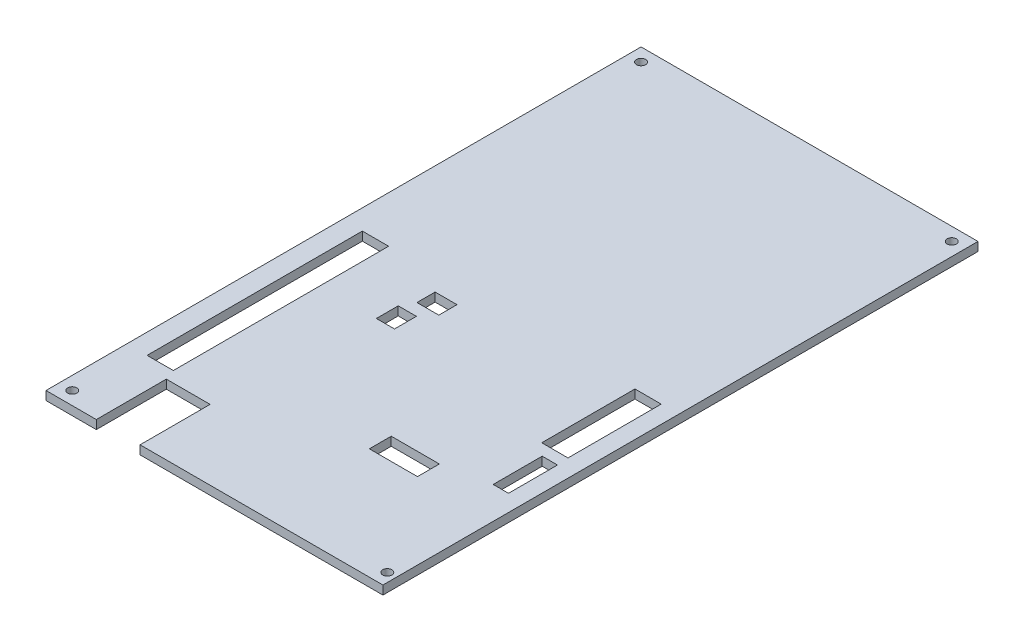
SolidWorks part; units mm, degrees
ref_plane "前视基准面" through (0, 0, 0) normal (0, 0, 1) x (1, 0, 0)
ref_plane "上视基准面" through (0, 0, 0) normal (0, 1, 0) x (1, 0, 0)
ref_plane "右视基准面" through (0, 0, 0) normal (1, 0, 0) x (0, 0, -1)
sketch "草图2" plane through (0, 0, 0) normal (0, 1, 0) x (1, 0, 0)
  line L0 (0, 0) -> (77, -136) construction
  line L1 (0, 0) -> (77, 0)
  line L2 (0, 0) -> (0, -136)
  line L3 (0, -136) -> (77, -136)
  line L4 (77, 0) -> (77, -136)
  line L5 (77, 0) -> (0, -136) construction
  line L6 (0, -3) -> (77, -3) construction
  line L12 (4.6, -68.3) -> (10.6, -68.3)
  line L13 (0, -133) -> (77, -133) construction
  line L14 (3, 0) -> (3, -136) construction
  line L15 (74, 0) -> (74, -136) construction
  line L16 (4.6, -68.3) -> (4.6, -117.5)
  line L29 (7, -12.5) -> (70, -123.5) construction
  line L30 (7, -123.5) -> (70, -12.5) construction
  line L31 (4.6, -117.5) -> (10.6, -117.5)
  line L32 (10.6, -68.3) -> (10.6, -117.5)
  line L33 (73, -68.4) -> (67, -68.4)
  line L34 (73, -68.4) -> (73, -89.7)
  line L35 (73, -89.7) -> (67, -89.7)
  line L36 (67, -68.4) -> (67, -89.7)
  line L37 (69.7, -92.3) -> (73.2, -92.3)
  line L38 (69.7, -92.3) -> (69.7, -103.5)
  line L39 (69.7, -103.5) -> (73.2, -103.5)
  line L40 (73.2, -92.3) -> (73.2, -103.5)
  line L41 (48.5, -105.6) -> (59.5, -105.6)
  line L42 (48.5, -105.6) -> (48.5, -110.6)
  line L43 (48.5, -110.6) -> (59.5, -110.6)
  line L44 (59.5, -105.6) -> (59.5, -110.6)
  line L45 (23.5, -79) -> (27.65, -79)
  line L46 (23.5, -79) -> (23.5, -84)
  line L47 (23.5, -84) -> (27.65, -84)
  line L48 (27.65, -79) -> (27.65, -84)
  line L49 (24.98, -72.05) -> (29.98, -72.05)
  line L50 (24.98, -72.05) -> (24.98, -76.2)
  line L51 (24.98, -76.2) -> (29.98, -76.2)
  line L52 (29.98, -72.05) -> (29.98, -76.2)
  line L53 (11.5, -136) -> (21.5, -136)
  line L54 (11.5, -136) -> (11.5, -120)
  line L55 (11.5, -120) -> (21.5, -120)
  line L56 (21.5, -136) -> (21.5, -120)
  circle A0 centre (3, -3) radius 1.05
  circle A1 centre (74, -3) radius 1.05
  circle A2 centre (3, -133) radius 1.05
  circle A3 centre (75, -133) radius 1.05
  point P5 (38.5, -68)
  point P26 (38.5, -68)
  dimension "D9" = 2.1
  dimension "D10" = 2.1
  dimension "D11" = 2.1
  dimension "D12" = 2.1
  dimension "D15" = 6
  dimension "D16" = 21.3
  dimension "D17" = 11.2
  dimension "D18" = 3.5
  dimension "D1" = 136
  dimension "D2" = 77
  dimension "D3" = 49.2
  dimension "D4" = 6
  dimension "D5" = 3
  dimension "D6" = 3
  dimension "D7" = 3
  dimension "D8" = 3
  dimension "D13" = 63
  dimension "D14" = 111
  dimension "D19" = 11
  dimension "D20" = 5
  dimension "D21" = 4.15
  dimension "D22" = 5
  dimension "D23" = 5
  dimension "D24" = 4.15
  dimension "D25" = 2.8
  dimension "D26" = 1.48
  dimension "D27" = 2
  dimension "D28" = 18.5
  dimension "D29" = 4.6
  dimension "D30" = 25.4
  dimension "D31" = 17.5
  dimension "D32" = 3.8
  dimension "D33" = 32.5
  dimension "D34" = 46.3
  dimension "D35" = 4
  dimension "D36" = 23.5
  dimension "D37" = 52
  dimension "D38" = 10
  dimension "D39" = 16
  dimension "D40" = 11.5
extrude "凸台-拉伸1" add sketch "草图2" along normal blind 2
